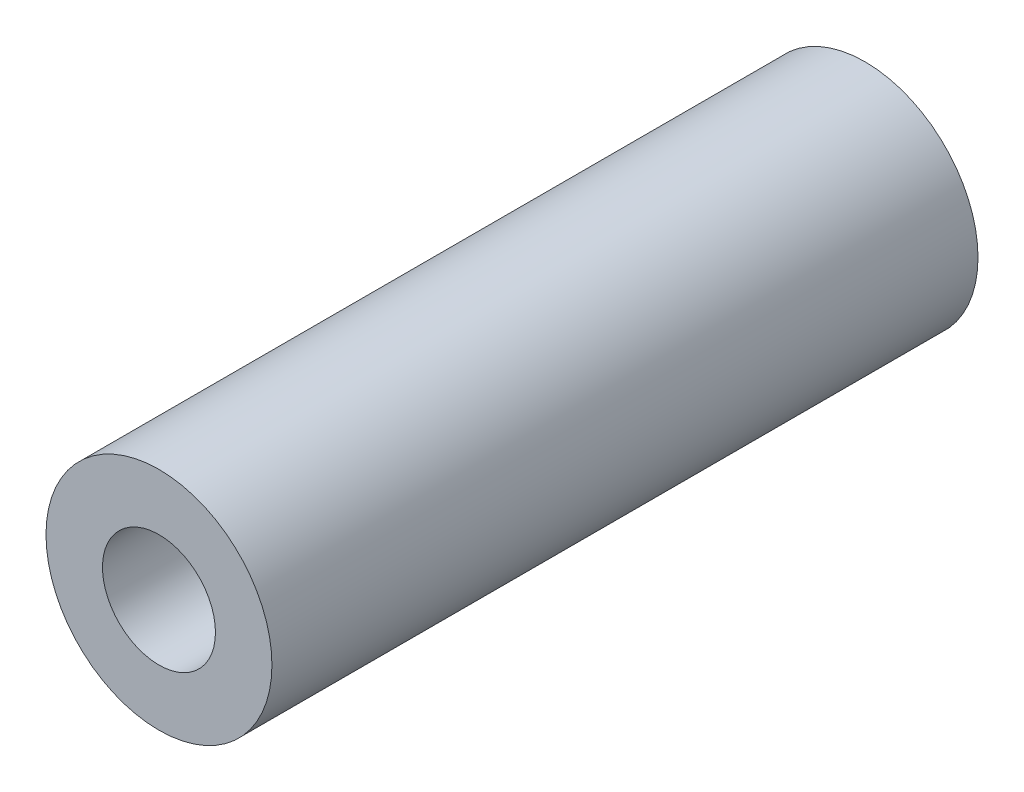
SolidWorks part; units mm, degrees
ref_plane "정면" through (0, 0, 0) normal (0, 0, 1) x (1, 0, 0)
ref_plane "윗면" through (0, 0, 0) normal (0, 1, 0) x (1, 0, 0)
ref_plane "우측면" through (0, 0, 0) normal (1, 0, 0) x (0, 0, -1)
sketch "스케치1" plane through (0, 0, 0) normal (0, 0, 1) x (1, 0, 0)
  circle A0 centre (0, 0) radius 8
  dimension "D1" = 16
extrude "보스-돌출1" add sketch "스케치1" along normal blind 50
sketch "스케치2" plane through (0, 0, 50) normal (0, 0, 1) x (1, 0, 0)
  circle A0 centre (0, 0) radius 4
  dimension "D1" = 8
extrude "컷-돌출1" cut sketch "스케치2" against normal blind 30
